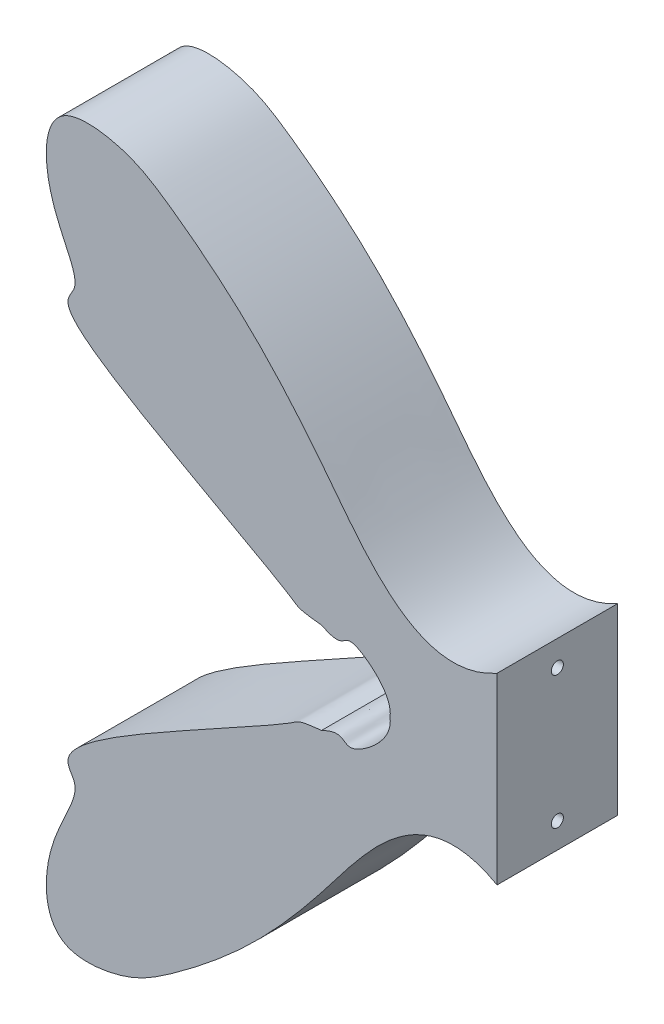
SolidWorks part; units mm, degrees
material "Silicon Rubber"
ref_plane "Front Plane" through (0, 0, 0) normal (0, 0, 1) x (1, 0, 0)
ref_plane "Top Plane" through (0, 0, 0) normal (0, 1, 0) x (1, 0, 0)
ref_plane "Right Plane" through (0, 0, 0) normal (1, 0, 0) x (0, 0, -1)
sketch "Sketch1" plane through (0, 0, 0) normal (0, 0, 1) x (1, 0, 0)
  line L0 (39.5185, 0) -> (0, 0) construction
  line L1 (71.6325, 15.1972) -> (71.6325, -15.1972)
  line L2 (39.5185, 0) -> (105.3226, 0) construction
  line L3 (79.5392, -10.3) -> (79.5392, 13.7) construction
  line L4 (152.4014, 17.5142) -> (152.4014, 31.0984) construction
  line L5 (163.4847, 19.8) -> (192.7256, 19.8) construction
  ellipse E0 centre (260.0208, 12.2) end of major axis (260.0208, 49.3603) minor radius 7.4598 construction
  ellipse E1 centre (149.0015, 6.1) end of major axis (149.0015, 31.1) minor radius 7.0004 construction
  spline S0 degree 3 poles (71.6325, 15.1972) (58.9739, 8.0992) (42.5681, 32.1576) (28.3615, 46.9536) (16.4402, 55.973) (10.1283, 59.7584) (-3.8944, 61.5978) (-3.7829, 46.5834) (4.7503, 33.6618) (-6.004, 32.3536) (39.7191, 8.2666) (38.5368, 8.0047) (42.5386, 7.5543) knots 0 0 0 0 0.127763 0.242355 0.328153 0.413845 0.506383 0.653086 0.740126 0.845653 0.902495 0.926083 0.926083 0.926083 0.926083
  spline S1 degree 3 poles (42.5386, 7.5543) (47.0321, 5.3096) (44.7789, 10.9369) (54.3379, 3.1343) (53.8927, 0) knots 0 0 0 0 0.786447 1.267001 1.267001 1.267001 1.267001
  spline S2 degree 3 poles (42.5386, -7.5543) (47.0321, -5.3096) (44.7789, -10.9369) (54.3379, -3.1343) (53.8927, 0) knots 0 0 0 0 0.786447 1.267001 1.267001 1.267001 1.267001
  spline S3 degree 3 poles (71.6325, -15.1972) (58.9739, -8.0992) (42.5681, -32.1576) (28.3615, -46.9536) (16.4402, -55.973) (10.1283, -59.7584) (-3.8944, -61.5978) (-3.7829, -46.5834) (4.7503, -33.6618) (-6.004, -32.3536) (39.7191, -8.2666) (38.5368, -8.0047) (42.5386, -7.5543) knots 0 0 0 0 0.127763 0.242355 0.328153 0.413845 0.506383 0.653086 0.740126 0.845653 0.902495 0.926083 0.926083 0.926083 0.926083
  point P2 (55.9165, 26.8204)
  point P4 (-18.5077, 83.4267)
  point P7 (45.7679, 6.9151)
  point P8 (-10.319, 42.9285)
  point P10 (53.8331, 1.4145)
  point P11 (56.9825, 15.3619)
  point P12 (-23.1622, 77.1486)
  point P13 (71.6325, 0)
  point P14 (71.6325, 0)
  point P15 (48.786, 7.1212)
  point P17 (45.7679, -6.9151)
  point P25 (53.9087, -0.9451)
  point P29 (53.9248, -0.7394)
  point P44 (36.8292, 48.7636)
  point P45 (41.8172, -7.6371)
  point P46 (34.5649, -40.2066)
  point P47 (53.9192, -0.8272)
  point P48 (71.6325, 0)
extrude "Boss-Extrude1" add sketch "Sketch1" along normal mid plane 20 contours S0 S1 S2 S3 L1
sketch "Sketch2" plane through (71.6325, 0, 0) normal (1, 0, 0) x (0, 0, -1)
  line L0 (-10, 0) -> (10, 0) construction
  line L1 (-10, 15.1972) -> (-10, -15.1972) construction
  line L2 (10, 15.1972) -> (10, -15.1972) construction
  circle A0 centre (0, 11) radius 1
  circle A1 centre (0, -11) radius 1
  dimension "D2" = 2
  dimension "D1" = 11
extrude "Cut-Extrude1" cut sketch "Sketch2" against normal blind 5
